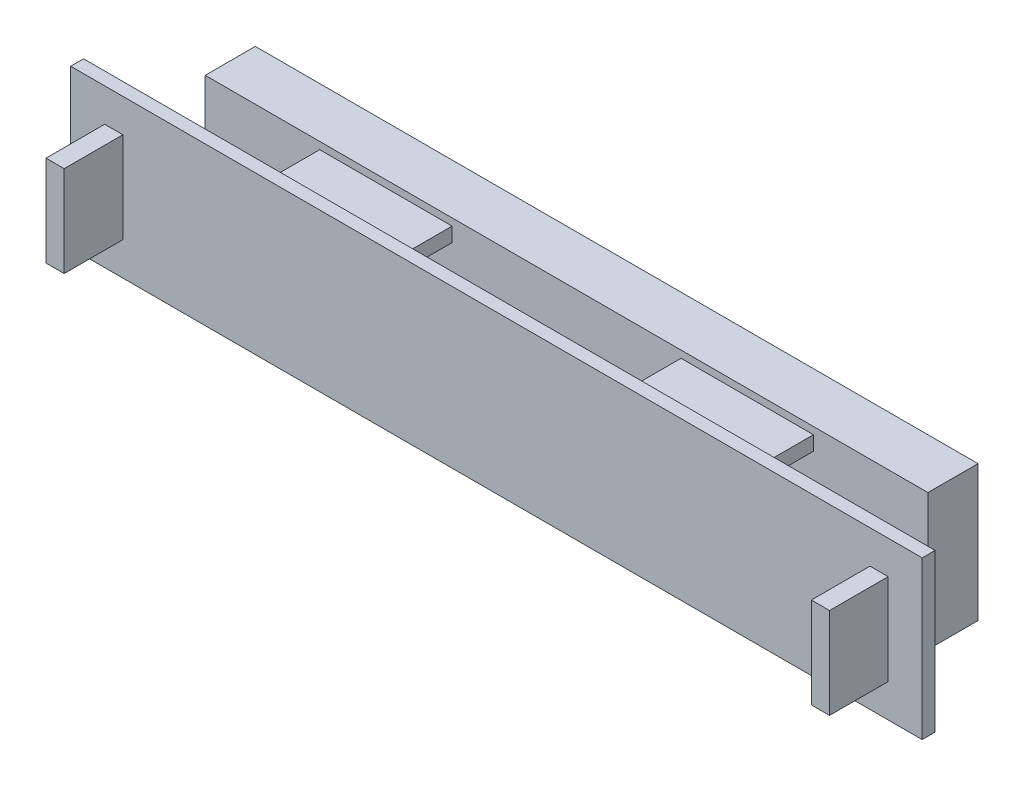
SolidWorks part; units mm, degrees
ref_plane "Plan de face" through (0, 0, 0) normal (0, 0, 1) x (1, 0, 0)
ref_plane "Plan de dessus" through (0, 0, 0) normal (0, 1, 0) x (1, 0, 0)
ref_plane "Plan de droite" through (0, 0, 0) normal (1, 0, 0) x (0, 0, -1)
sketch "Esquisse1" plane through (0, 0, 0) normal (0, 0, 1) x (1, 0, 0)
  line L1 (-50.5, -9.5) -> (50.5, -9.5)
  line L2 (-50.5, -9.5) -> (-50.5, 9.5)
  line L3 (-50.5, 9.5) -> (50.5, 9.5)
  line L4 (50.5, -9.5) -> (50.5, 9.5)
  line L5 (-50.5, -9.5) -> (50.5, 9.5) construction
  line L6 (-50.5, 9.5) -> (50.5, -9.5) construction
  point P0 (0, 0)
  dimension "D1" = 101
  dimension "D2" = 19
extrude "Boss.-Extru.1" add sketch "Esquisse1" along normal blind 15
sketch "Esquisse2" plane through (0, 0, 15) normal (0, 0, 1) x (1, 0, 0)
  line L1 (-59.5, -11) -> (59.5, -11)
  line L2 (-59.5, -11) -> (-59.5, 11)
  line L3 (-59.5, 11) -> (59.5, 11)
  line L4 (59.5, -11) -> (59.5, 11)
  line L5 (-59.5, -11) -> (59.5, 11) construction
  line L6 (-59.5, 11) -> (59.5, -11) construction
  point P0 (0, 0)
  dimension "D1" = 119
  dimension "D2" = 22
extrude "Boss.-Extru.2" add sketch "Esquisse2" along normal blind 1.8
sketch "Esquisse3" plane through (0, 9.5, 0) normal (0, 1, 0) x (1, 0, 0)
  line L0 (0, 0) -> (0, -39.3108) construction
  line L1 (-50.5, -15) -> (-34.5, -15)
  line L2 (-50.5, -15) -> (-50.5, -7)
  line L3 (-50.5, -7) -> (-34.5, -7)
  line L4 (-34.5, -15) -> (-34.5, -7)
  line L5 (-50.5, 0) -> (0, 0) construction
  line L6 (-25.25, 0) -> (-25.25, -28.7032) construction
  line L7 (-16, -15) -> (-16, -7)
  line L8 (16, -7) -> (-16, -7)
  line L9 (0, -15) -> (0, -7)
  line L10 (16, -15) -> (-16, -15)
  line L11 (34.5, -15) -> (34.5, -7)
  line L12 (50.5, -7) -> (34.5, -7)
  line L13 (50.5, -15) -> (50.5, -7)
  line L14 (50.5, -15) -> (34.5, -15)
  line L15 (16, -15) -> (16, -7)
  line M2 (-50.5, 0) -> (-50.5, -15)
  line M3 (-50.5, -15) -> (50.5, -15)
  line M4 (50.5, -15) -> (50.5, 0)
  dimension "D1" = 16
  dimension "D2" = 8
extrude "Enlèv. mat.-Extru.1" cut sketch "Esquisse3" against normal through all contours L9 L8 L7 M3 | L15 L8 L9 M3 | L12 L11 M4 M3 | L4 L3 M3 M2
sketch "Esquisse4" plane through (-34.5, 0, 0) normal (-1, 0, 0) x (0, 0, 1)
  line L0 (15, -9.5) -> (15, 9.5) construction
  line L1 (7, 9.5) -> (15, 9.5)
  line L2 (7, 9.5) -> (7, 8.5)
  line L3 (7, 8.5) -> (15, 8.5)
  line L4 (15, 9.5) -> (15, 8.5)
  line L5 (7, -9.5) -> (7, 9.5) construction
  line L6 (7, 6.5) -> (15, 6.5)
  line L7 (7, 6.5) -> (7, -6.5)
  line L8 (7, -6.5) -> (15, -6.5)
  line L9 (15, 6.5) -> (15, -6.5)
  line L10 (15, 11) -> (15, -11) construction
  line L11 (0, 0) -> (25.8484, 0) construction
  line L12 (7, -9.5) -> (15, -9.5)
  line L13 (7, -9.5) -> (7, -8.5)
  line L14 (7, -8.5) -> (15, -8.5)
  line L15 (15, -9.5) -> (15, -8.5)
  dimension "D1" = 1
  dimension "D2" = 2
extrude "Enlèv. mat.-Extru.2" cut sketch "Esquisse4" against normal through all
sketch "Esquisse5" plane through (0, 0, 15) normal (0, 0, -1) x (-1, 0, 0)
  line L1 (14, 5) -> (-14, 5)
  line L2 (14, 5) -> (14, -5)
  line L3 (14, -5) -> (-14, -5)
  line L4 (-14, 5) -> (-14, -5)
  line L5 (14, 5) -> (-14, -5) construction
  line L6 (14, -5) -> (-14, 5) construction
  point P0 (0, 0)
  dimension "D1" = 28
  dimension "D2" = 10
extrude "Boss.-Extru.3" add sketch "Esquisse5" along normal blind 6
sketch "Esquisse7" plane through (0, 0, 15) normal (0, 0, -1) x (-1, 0, 0)
  line L0 (-59.5, -11) -> (-59.5, 11) construction
  line L1 (-54.75, 6.35) -> (-52.21, 6.35)
  line L2 (-54.75, 6.35) -> (-54.75, -6.35)
  line L3 (-54.75, -6.35) -> (-52.21, -6.35)
  line L4 (-52.21, 6.35) -> (-52.21, -6.35)
  line L5 (-59.5, 0) -> (59.5, 0) construction
  line L6 (59.5, 11) -> (59.5, -11) construction
  line L7 (0, -11) -> (0, 11) construction
  line L8 (59.5, -11) -> (-59.5, -11) construction
  line L9 (-59.5, 11) -> (59.5, 11) construction
  line L10 (52.21, 6.35) -> (52.21, -6.35)
  line L11 (54.75, -6.35) -> (52.21, -6.35)
  line L12 (54.75, 6.35) -> (54.75, -6.35)
  line L13 (54.75, 6.35) -> (52.21, 6.35)
  point P11 (-54.75, 0)
  point P21 (54.75, 0)
  dimension "D1" = 4.75
  dimension "D2" = 2.54
  dimension "D3" = 12.7
extrude "Boss.-Extru.4" add sketch "Esquisse7" against normal blind 10
